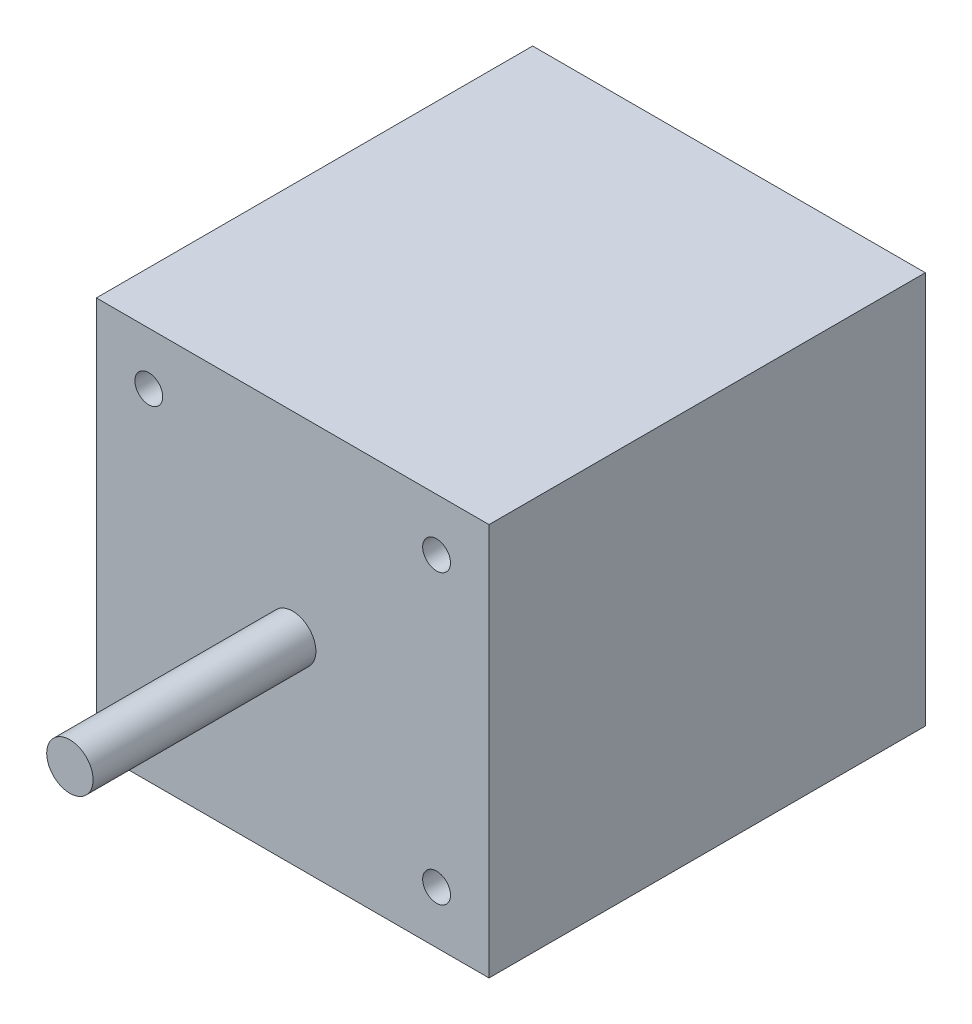
SolidWorks part; units mm, degrees
ref_plane "Front Plane" through (0, 0, 0) normal (0, 0, 1) x (1, 0, 0)
ref_plane "Top Plane" through (0, 0, 0) normal (0, 1, 0) x (1, 0, 0)
ref_plane "Right Plane" through (0, 0, 0) normal (1, 0, 0) x (0, 0, -1)
sketch "Sketch1" plane through (0, 0, 0) normal (0, 0, 1) x (1, 0, 0)
  line L1 (0, 0) -> (42.3, 0)
  line L2 (0, 0) -> (0, 42.3)
  line L3 (0, 42.3) -> (42.3, 42.3)
  line L4 (42.3, 0) -> (42.3, 42.3)
  dimension "D1" = 42.3
  dimension "D2" = 42.3
extrude "Boss-Extrude1" add sketch "Sketch1" along normal blind 47
sketch "Sketch2" plane through (0, 0, 47) normal (0, 0, 1) x (1, 0, 0)
  line L0 (42.3, 42.3) -> (0, 42.3) construction
  line L1 (0, 42.3) -> (0, 0) construction
  circle A0 centre (21.15, 21.15) radius 2.5
  point P2 (0, 0)
  point P5 (21.15, 42.3)
  point P6 (0, 0)
  point P9 (0, 21.15)
  dimension "D1" = 5
extrude "Boss-Extrude2" add sketch "Sketch2" along normal blind 24
sketch "Sketch3" plane through (0, 0, 47) normal (0, 0, 1) x (1, 0, 0)
  circle A0 centre (5.65, 36.65) radius 1.5
  circle A1 centre (36.65, 36.65) radius 1.5
  circle A2 centre (36.65, 5.65) radius 1.5
  circle A3 centre (5.65, 5.65) radius 1.5
  circle A4 centre (21.15, 21.15) radius 2.5 construction
  point P2 (35.0511, 3.4363)
  point P3 (0, 0)
  point P11 (21.15, 21.15)
  point P13 (5.4982, 5.8018)
  point P14 (0, 0)
  point P15 (0, 0)
  dimension "D2" = 31
  dimension "D3" = 3
  dimension "D1" = 4
extrude "Cut-Extrude1" cut sketch "Sketch3" against normal blind 4.5
